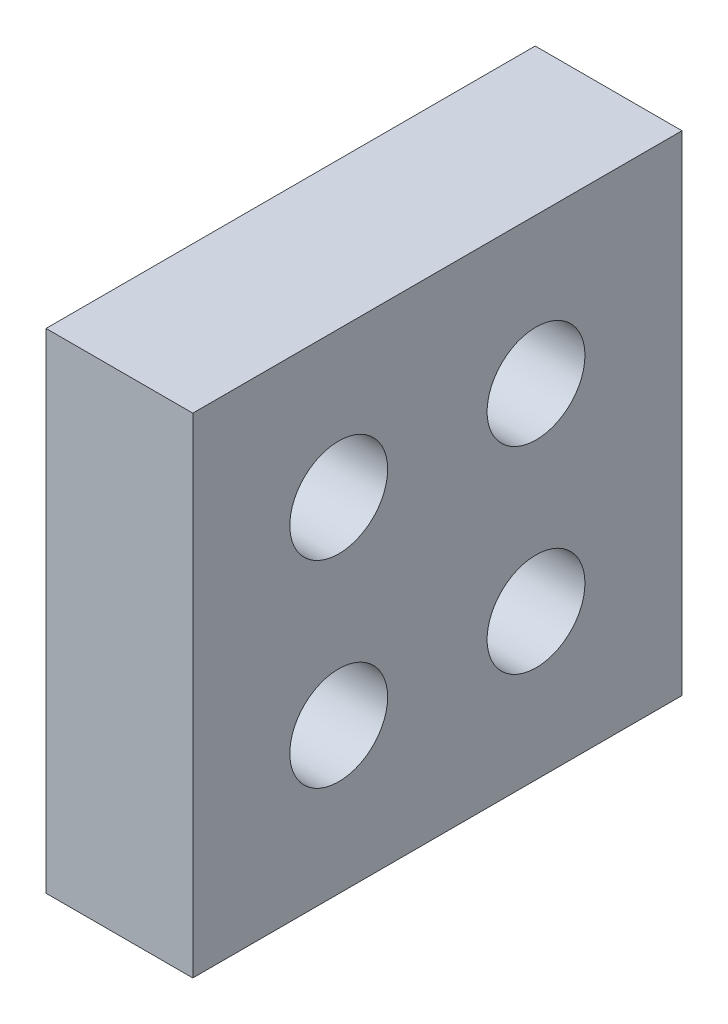
SolidWorks part; units mm, degrees
material "Balsa"
ref_plane "Front Plane" through (0, 0, 0) normal (1, 0, 0) x (0, 1, 0)
ref_plane "Top Plane" through (0, 0, 0) normal (0, 0, 1) x (0, 1, 0)
ref_plane "Right Plane" through (0, 0, 0) normal (0, 1, 0) x (-1, 0, 0)
sketch "Sketch1" plane through (0, 0, 0) normal (1, 0, 0) x (0, 1, 0)
  line L0 (-15, -15) -> (-15, 15)
  line L1 (-11, -11) -> (11, -11)
  line L2 (-11, -11) -> (-11, 11)
  line L3 (-11, 11) -> (11, 11)
  line L4 (11, -11) -> (11, 11)
  line L5 (-11, -11) -> (11, 11) construction
  line L6 (-11, 11) -> (11, -11) construction
  line L7 (-15, 15) -> (15, 15)
  line L8 (15, -15) -> (15, 15)
  line L9 (-15, -15) -> (15, -15)
  line L10 (11, 0) -> (-11, 0) construction
  line L12 (0, -11) -> (0, 11) construction
  circle A0 centre (6.0503, 6.0503) radius 3
  circle A1 centre (-6.0503, 6.0503) radius 3
  circle A2 centre (-6.0503, -6.0503) radius 3
  circle A3 centre (6.0503, -6.0503) radius 3
  point P0 (0, 0)
  dimension "D4" = 6
  dimension "D1" = 22
  dimension "D2" = 22
  dimension "D5" = 7
  dimension "D3" = 4
extrude "Boss-Extrude1" add sketch "Sketch1" along normal blind 9
